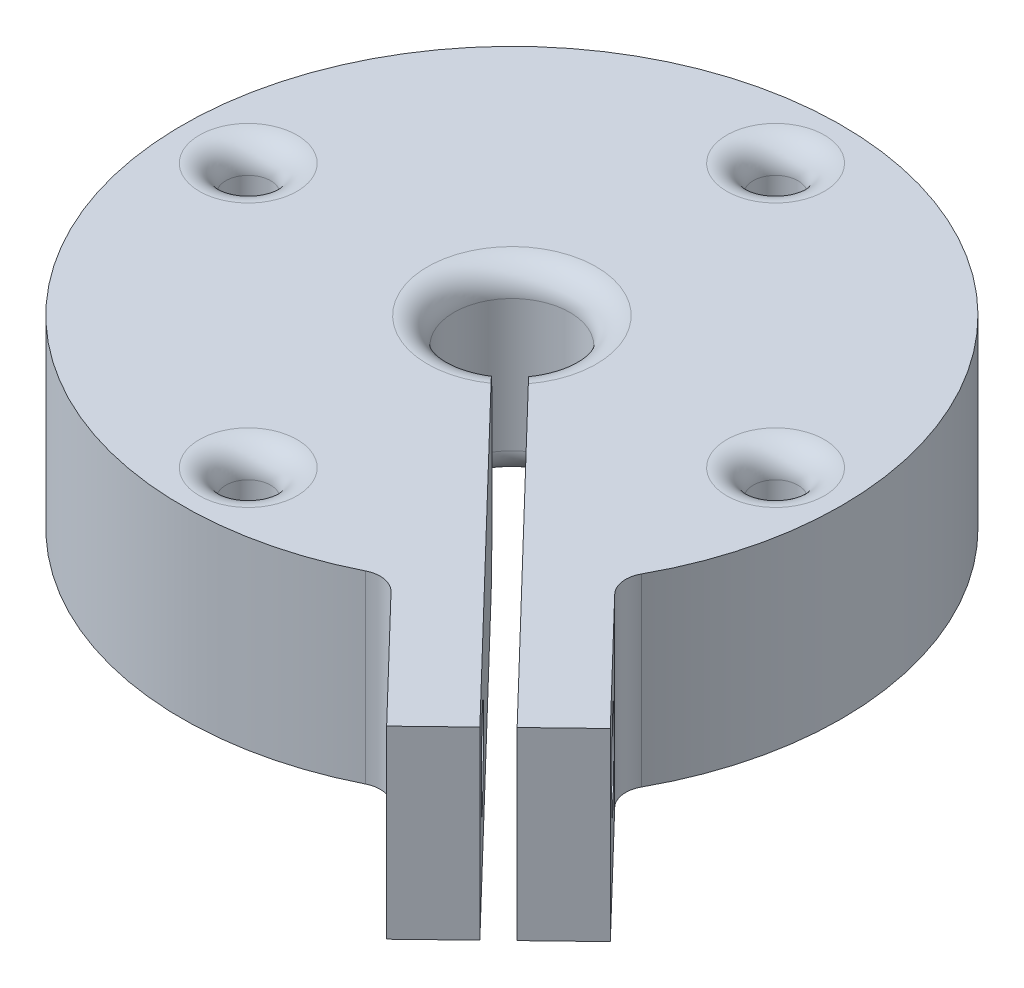
SolidWorks part; units mm, degrees
ref_plane "前视基准面" through (0, 0, 0) normal (0, 0, 1) x (1, 0, 0)
ref_plane "上视基准面" through (0, 0, 0) normal (0, 1, 0) x (1, 0, 0)
ref_plane "右视基准面" through (0, 0, 0) normal (1, 0, 0) x (0, 0, -1)
sketch "草图1" plane through (0, 0, 0) normal (0, 1, 0) x (1, 0, 0)
  circle A0 centre (0, 0) radius 12.5
  circle A1 centre (0, 0) radius 2.2
  circle A2 centre (0, 10) radius 0.85
  circle A3 centre (10, 0) radius 0.85
  circle A4 centre (0, -10) radius 0.85
  circle A5 centre (-10, 0) radius 0.85
  point P15 (0, 0)
  dimension "D1" = 4.4
  dimension "D2" = 1.7
  dimension "D5" = 25
  dimension "D4" = 10
  dimension "D3" = 4
extrude "凸台-拉伸1" add sketch "草图1" along normal blind 7
fillet "圆角1" radius 1 10 edges at (10, 0, 0.85) (0, 0, 10.85) (0, 0, -9.15) (0, 0, 2.2) (-10, 0, 0.85) (10, 7, 0.85) (0, 7, -9.15) (0, 7, 2.2) (0, 7, 10.85) (-10, 7, 0.85)
sketch "草图2" plane through (0, 7, 0) normal (0, 1, 0) x (1, 0, 0)
  line L0 (0, 0) -> (13.2734, -13.7823) construction
  line L1 (13.2734, -13.7823) -> (15.4342, -11.7013)
  line L2 (15.4342, -11.7013) -> (10.5784, -6.6593)
  line L3 (10.5784, -6.6593) -> (6.2568, -10.8214)
  line L4 (6.2568, -10.8214) -> (11.1125, -15.8634)
  line L5 (11.1125, -15.8634) -> (13.2734, -13.7823)
  circle A0 centre (0, 0) radius 12.5 construction
  dimension "D1" = 7
  dimension "D2" = 6
extrude "凸台-拉伸2" add sketch "草图2" against normal up to surface (7 mm away) up to face at (10, 0, 1.85)
sketch "草图3" plane through (0, 7, 0) normal (0, 1, 0) x (1, 0, 0)
  line L0 (13.2734, -13.7823) -> (0, 0) construction
  line L1 (11.1125, -15.8634) -> (15.4342, -11.7013) construction
  line L2 (13.2734, -13.7823) -> (13.6335, -13.4355)
  line L3 (13.6335, -13.4355) -> (1.0829, -0.4037)
  line L4 (1.0829, -0.4037) -> (0.3627, -1.0973)
  line L5 (0.3627, -1.0973) -> (12.9132, -14.1292)
  line L6 (12.9132, -14.1292) -> (13.2734, -13.7823)
  dimension "D1" = 1
extrude "切除-拉伸1" cut sketch "草图3" against normal through all
sketch "草图4" plane through (2.1608, 0, -2.081) normal (0.7203, 0, -0.6937) x (-0.6937, 0, -0.7203)
  circle A0 centre (-15.5329, 3.4619) radius 1.6
  dimension "D1" = 3.2
extrude "切除-拉伸2" cut sketch "草图4" against normal through all
fillet "圆角2" radius 1 2 edges at (10.5784, 3.5, 6.6593) (6.2568, 3.5, 10.8214)
